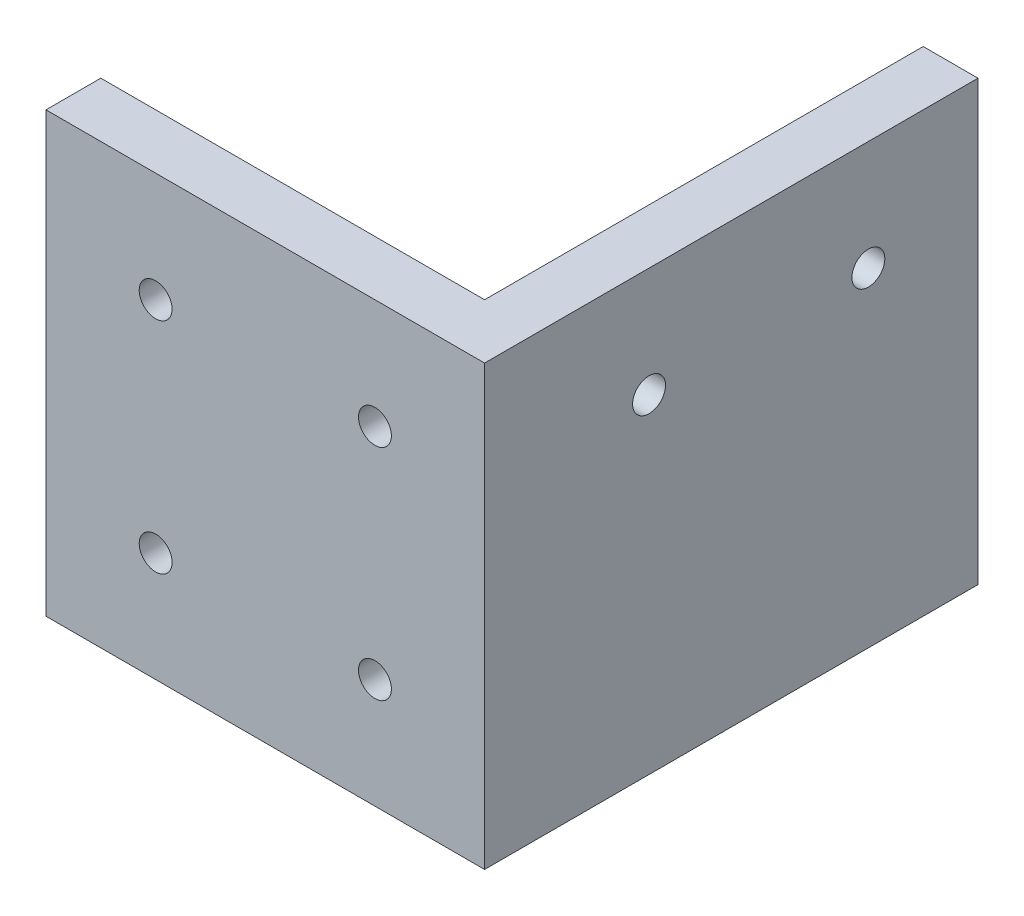
SolidWorks part; units mm, degrees
ref_plane "Front Plane" through (0, 0, 0) normal (0, 0, 1) x (1, 0, 0)
ref_plane "Top Plane" through (0, 0, 0) normal (0, 1, 0) x (1, 0, 0)
ref_plane "Right Plane" through (0, 0, 0) normal (1, 0, 0) x (0, 0, -1)
sketch "Sketch1" plane through (0, 0, 0) normal (0, 0, 1) x (1, 0, 0)
  line L0 (0, 0) -> (0, 95)
  line L1 (0, 95) -> (20, 95)
  line L2 (20, 95) -> (20, 75)
  line L3 (20, 75) -> (40, 75)
  line L4 (40, 75) -> (40, 80)
  line L5 (40, 80) -> (50, 80)
  line L6 (50, 80) -> (50, 75)
  line L7 (50, 75) -> (70, 75)
  line L8 (70, 75) -> (70, 80)
  line L9 (70, 80) -> (80, 80)
  line L10 (80, 80) -> (80, 15)
  line L11 (80, 15) -> (445, 15)
  line L23 (237.9167, 0) -> (0, 0)
  line L24 (262.5, 146.857) -> (262.5, -30.5268)
  line L25 (287.0833, 0) -> (525, 0)
  line L26 (445, 80) -> (445, 15)
  line L27 (455, 80) -> (445, 80)
  line L28 (455, 75) -> (455, 80)
  line L29 (475, 75) -> (455, 75)
  line L30 (485, 80) -> (475, 80)
  line L31 (485, 75) -> (485, 80)
  line L32 (505, 75) -> (485, 75)
  line L33 (505, 95) -> (505, 75)
  line L34 (525, 95) -> (505, 95)
  line L35 (525, 0) -> (525, 95)
  line L36 (475, 75) -> (475, 80)
  line L37 (237.9167, 0) -> (287.0833, 0)
  point P19 (262.5, 15)
  dimension "D1" = 10
  dimension "D2" = 10
  dimension "D3" = 182.5
  dimension "D4" = 20
  dimension "D5" = 20
  dimension "D6" = 20
  dimension "D7" = 20
  dimension "D8" = 5
  dimension "D9" = 5
  dimension "D10" = 65
  dimension "D11" = 80
  dimension "D12" = 95
extrude "Boss-Extrude1" add sketch "Sketch1" along normal blind 597.1 contours L23 L37 L24 L11 L10 L9 L8 L7 L6 L5 L4 L3 L2 L1 L0 | L24 L37 L25 L35 L34 L33 L32 L31 L30 L36 L29 L28 L27 L26 L11
sketch "Sketch2" plane through (0, 15, 0) normal (0, 1, 0) x (1, 0, 0)
  line L0 (80, 0) -> (445, 0) construction
  line L1 (187.3, 0) -> (252.5, 0)
  line L2 (187.3, 0) -> (187.3, -400)
  line L3 (187.3, -400) -> (252.5, -400)
  line L4 (252.5, 0) -> (252.5, -400)
  line L5 (80, -597.1) -> (445, -597.1) construction
  line L6 (272.5, -597.1) -> (337.7, -597.1)
  line L7 (272.5, -597.1) -> (272.5, -197.1)
  line L8 (272.5, -197.1) -> (337.7, -197.1)
  line L9 (337.7, -597.1) -> (337.7, -197.1)
  line L10 (445, -597.1) -> (445, 0) construction
  dimension "D1" = 400
  dimension "D2" = 400
  dimension "D3" = 65.2
  dimension "D4" = 65.2
  dimension "D5" = 20
  dimension "D6" = 107.3
extrude "Cut-Extrude1" cut sketch "Sketch2" against normal through all
sketch "Sketch3" plane through (0, 15, 0) normal (0, 1, 0) x (1, 0, 0)
  line L1 (80, 0) -> (445, 0)
  line L2 (80, 0) -> (80, -597.1)
  line L3 (80, -597.1) -> (445, -597.1)
  line L4 (445, 0) -> (445, -597.1)
  line L5 (187.3, 0) -> (252.5, 0)
  line L6 (187.3, 0) -> (187.3, -400)
  line L7 (187.3, -400) -> (252.5, -400)
  line L8 (252.5, 0) -> (252.5, -400)
  line L9 (272.5, -197.1) -> (337.7, -197.1)
  line L10 (272.5, -197.1) -> (272.5, -597.1)
  line L11 (272.5, -597.1) -> (337.7, -597.1)
  line L12 (337.7, -197.1) -> (337.7, -597.1)
  line M1 (187.3, -400) -> (187.3, 0)
  line M2 (187.3, 0) -> (80, 0)
  line M3 (80, 0) -> (80, -597.1)
  line M4 (80, -597.1) -> (272.5, -597.1)
  line M5 (272.5, -597.1) -> (272.5, -197.1)
  line M6 (272.5, -197.1) -> (337.7, -197.1)
  line M7 (337.7, -197.1) -> (337.7, -597.1)
  line M8 (337.7, -597.1) -> (445, -597.1)
  line M9 (445, -597.1) -> (445, 0)
  line M10 (445, 0) -> (252.5, 0)
  line M11 (252.5, 0) -> (252.5, -400)
  line M12 (252.5, -400) -> (187.3, -400)
extrude "Boss-Extrude2" add sketch "Sketch3" along normal blind 8 contours M12 M1 M2 M3 M4 M5 M6 M7 M8 M9 M10 M11
sketch "Sketch4" plane through (0, 0, 0) normal (0, -1, 0) x (1, 0, 0)
  line L1 (0, 597.1) -> (525, 597.1)
  line L2 (0, 597.1) -> (0, 0)
  line L3 (0, 0) -> (525, 0)
  line L4 (525, 597.1) -> (525, 0)
extrude "Boss-Extrude3" add sketch "Sketch4" along normal blind 7
sketch "Sketch5" plane through (0, 23, 0) normal (0, 1, 0) x (1, 0, 0)
  line L1 (80, 0) -> (445, 0)
  line L2 (80, 0) -> (80, -597.1)
  line L3 (80, -597.1) -> (445, -597.1)
  line L4 (445, 0) -> (445, -597.1)
extrude "Cut-Extrude2" cut sketch "Sketch5" against normal blind 10
sketch "Sketch6" plane through (525, 0, 0) normal (1, 0, 0) x (0, 0, -1)
  line L0 (-597.1, 95) -> (0, 95) construction
  line L1 (-324.55, 95) -> (-272.55, 95)
  line L2 (-324.55, 95) -> (-324.55, 55)
  line L3 (-324.55, 55) -> (-272.55, 55)
  line L4 (-272.55, 95) -> (-272.55, 55)
  line L6 (-597.1, -7) -> (-597.1, 95) construction
  circle A0 centre (-318.55, 79) radius 2.125
  circle A1 centre (-278.55, 79) radius 2.125
  circle A2 centre (-278.55, 63) radius 2.125
  circle A3 centre (-318.55, 63) radius 2.125
  circle A4 centre (-318.55, 79) radius 2.125
  circle A5 centre (-278.55, 79) radius 2.125
  circle A6 centre (-278.55, 63) radius 2.125
  circle A7 centre (-318.55, 63) radius 2.125
  dimension "D4" = 4.25
  dimension "D1" = 52
  dimension "D2" = 40
  dimension "D3" = 272.55
  dimension "D5" = 40
  dimension "D6" = 40
  dimension "D7" = 16
  dimension "D8" = 16
  dimension "D9" = 6
  dimension "D10" = 8
extrude "Cut-Extrude3" cut sketch "Sketch6" against normal up to next contours A0 | A3 | A2 | A1
cosmetic thread "Cosmetic Thread5" parameters "D2"=5.5
cosmetic thread "Cosmetic Thread6" parameters "D2"=5.5
cosmetic thread "Cosmetic Thread7" parameters "D2"=5.5
cosmetic thread "Cosmetic Thread8" parameters "D2"=5.5
sketch "Sketch7" plane through (0, 75, 0) normal (0, 1, 0) x (1, 0, 0)
  line L1 (485, 0) -> (505, 0)
  line L2 (485, 0) -> (485, -597.1)
  line L3 (485, -597.1) -> (505, -597.1)
  line L4 (505, 0) -> (505, -597.1)
extrude "Cut-Extrude4" cut sketch "Sketch7" against normal blind 5
sketch "Sketch8" plane through (445, 0, 0) normal (-1, 0, 0) x (0, 0, 1)
  line L0 (597.1, 80) -> (0, 80) construction
  line L1 (269.8676, 50) -> (324.923, 50)
  line L2 (269.8676, 50) -> (269.8676, 70)
  line L3 (269.8676, 70) -> (324.923, 70)
  line L4 (324.923, 50) -> (324.923, 70)
  dimension "D1" = 20
  dimension "D2" = 55.0555
  dimension "D3" = 10
extrude "Cut-Extrude6" cut sketch "Sketch8" against normal blind 60
sketch "Sketch13" plane through (0, 50, 0) normal (0, 1, 0) x (1, 0, 0)
  line L0 (445, -269.8676) -> (445, -324.923) construction
  line L1 (445, -290.3007) -> (485, -290.3007)
  line L2 (445, -290.3007) -> (445, -305.3007)
  line L3 (445, -305.3007) -> (485, -305.3007)
  line L4 (485, -290.3007) -> (485, -305.3007)
  dimension "D1" = 15
  dimension "D2" = 40
extrude "Boss-Extrude4" add sketch "Sketch13" along normal up to next
sketch "Sketch14" plane through (0, 75, 0) normal (0, 1, 0) x (1, 0, 0)
  line L1 (20, 0) -> (40, 0)
  line L2 (20, 0) -> (20, -597.1)
  line L3 (20, -597.1) -> (40, -597.1)
  line L4 (40, 0) -> (40, -597.1)
extrude "Cut-Extrude7" cut sketch "Sketch14" against normal blind 5
sketch "Sketch15" plane through (0, 0, 0) normal (-1, 0, 0) x (0, 0, 1)
  line L0 (597.1, 95) -> (0, 95) construction
  line L1 (10, 95) -> (37, 95)
  line L2 (10, 95) -> (10, 49.6)
  line L3 (10, 49.6) -> (37, 49.6)
  line L4 (37, 95) -> (37, 49.6)
  line L5 (0, -7) -> (0, 95) construction
  line L10 (298.55, -7) -> (298.55, 95)
  line L11 (597.1, -7) -> (0, -7) construction
  line L12 (587.1, 49.6) -> (560.1, 49.6)
  line L13 (587.1, 95) -> (560.1, 95)
  line L14 (587.1, 95) -> (587.1, 49.6)
  line L15 (560.1, 95) -> (560.1, 49.6)
  circle A0 centre (13.5, 82.3) radius 1.33
  circle A1 centre (33.5, 82.3) radius 1.33
  circle A2 centre (33.5, 62.3) radius 1.33
  circle A3 centre (13.5, 62.3) radius 1.33
  circle A4 centre (563.6, 62.3) radius 1.33
  circle A5 centre (563.6, 82.3) radius 1.33
  circle A6 centre (583.6, 82.3) radius 1.33
  circle A7 centre (583.6, 62.3) radius 1.33
  circle A8 centre (13.5, 82.3) radius 1.33
  circle A9 centre (33.5, 82.3) radius 1.33
  circle A10 centre (33.5, 62.3) radius 1.33
  circle A11 centre (13.5, 62.3) radius 1.33
  dimension "D2" = 2.66
  dimension "D1" = 10
  dimension "D3" = 45.4
  dimension "D4" = 27
  dimension "D5" = 20
  dimension "D6" = 20
  dimension "D7" = 20
  dimension "D8" = 20
  dimension "D9" = 3.5
  dimension "D10" = 12.7
extrude "Cut-Extrude8" cut sketch "Sketch15" against normal up to next contours A0 | A1 | A3 | A2 | A5 | A7 | A4 | A6
cosmetic thread "Cosmetic Thread9" parameters "D2"=3.2
cosmetic thread "Cosmetic Thread10" parameters "D2"=3.2
cosmetic thread "Cosmetic Thread11" parameters "D2"=3.2
cosmetic thread "Cosmetic Thread12" parameters "D2"=3.2
cosmetic thread "Cosmetic Thread13" parameters "D2"=3.2
cosmetic thread "Cosmetic Thread14" parameters "D2"=3.2
cosmetic thread "Cosmetic Thread15" parameters "D2"=3.2
cosmetic thread "Cosmetic Thread16" parameters "D2"=3.2
sketch "Sketch16" plane through (80, 0, 0) normal (1, 0, 0) x (0, 0, -1)
  line L0 (-597.1, 80) -> (-597.1, 13) construction
  line L1 (-592.1, 70) -> (-557.1, 70)
  line L2 (-592.1, 70) -> (-592.1, 55)
  line L3 (-592.1, 55) -> (-557.1, 55)
  line L4 (-557.1, 70) -> (-557.1, 55)
  line L5 (-597.1, 80) -> (0, 80) construction
  line L6 (0, 80) -> (0, 13) construction
  line L7 (-40, 55) -> (-5, 55)
  line L8 (-40, 55) -> (-40, 70)
  line L9 (-40, 70) -> (-5, 70)
  line L10 (-5, 55) -> (-5, 70)
  dimension "D1" = 5
  dimension "D2" = 15
  dimension "D3" = 10
  dimension "D4" = 35
  dimension "D5" = 10
  dimension "D6" = 5
  dimension "D7" = 35
  dimension "D8" = 15
extrude "Cut-Extrude9" cut sketch "Sketch16" against normal blind 60
sketch "Sketch17" plane through (0, -7, 0) normal (0, -1, 0) x (1, 0, 0)
  line L0 (525, 0) -> (525, 597.1) construction
  line L1 (465, 373.55) -> (525, 373.55)
  line L2 (465, 373.55) -> (465, 223.55)
  line L3 (465, 223.55) -> (525, 223.55)
  line L4 (525, 373.55) -> (525, 223.55)
  line L5 (525, 597.1) -> (0, 597.1) construction
  dimension "D1" = 150
  dimension "D2" = 223.55
  dimension "D3" = 60
extrude "Cut-Extrude10" cut sketch "Sketch17" against normal blind 40
sketch "Sketch18" plane through (0, 13, 0) normal (0, 1, 0) x (1, 0, 0)
  line L1 (427, -286.05) -> (415, -286.05)
  line L2 (427, -286.05) -> (427, -302.05)
  line L3 (427, -302.05) -> (415, -302.05)
  line L4 (415, -286.05) -> (415, -302.05)
  line L5 (417, -286.05) -> (425, -286.05)
  line L6 (445, 0) -> (252.5, 0) construction
  line L7 (417, -286.05) -> (417, -279.05)
  line L8 (445, -597.1) -> (445, 0) construction
  line L9 (417, -279.05) -> (425, -279.05)
  line L10 (425, -286.05) -> (425, -279.05)
  line L11 (417, -302.05) -> (425, -302.05)
  line L12 (417, -302.05) -> (417, -309.05)
  line L13 (417, -309.05) -> (425, -309.05)
  line L14 (425, -302.05) -> (425, -309.05)
  dimension "D1" = 12
  dimension "D2" = 16
  dimension "D3" = 286.05
  dimension "D4" = 30
  dimension "D5" = 8
  dimension "D6" = 7
  dimension "D7" = 2
  dimension "D8" = 8
  dimension "D9" = 7
  dimension "D10" = 2
extrude "Cut-Extrude11" cut sketch "Sketch18" against normal through all contours L1 L4 L3 L2
sketch "Sketch19" plane through (0, 13, 0) normal (0, 1, 0) x (1, 0, 0)
  line L0 (427, -286.05) -> (415, -286.05) construction
  line L1 (417, -286.05) -> (425, -286.05)
  line L2 (417, -286.05) -> (417, -279.05)
  line L3 (417, -279.05) -> (425, -279.05)
  line L4 (425, -286.05) -> (425, -279.05)
  line L5 (427, -302.05) -> (415, -302.05) construction
  line L6 (417, -302.05) -> (425, -302.05)
  line L7 (417, -302.05) -> (417, -309.05)
  line L8 (417, -309.05) -> (425, -309.05)
  line L9 (425, -302.05) -> (425, -309.05)
  line L10 (415, -286.05) -> (415, -302.05) construction
  dimension "D1" = 8
  dimension "D2" = 8
  dimension "D3" = 7
  dimension "D4" = 7
  dimension "D5" = 2
  dimension "D6" = 2
extrude "Cut-Extrude12" cut sketch "Sketch19" against normal blind 10
sketch "Sketch20" plane through (525, 0, 0) normal (1, 0, 0) x (0, 0, -1)
  circle A0 centre (-318.55, 79) radius 2.7599
  circle A1 centre (-318.55, 63) radius 2.758
  circle A2 centre (-278.55, 63) radius 2.7761
  circle A3 centre (-278.55, 79) radius 2.7514
extrude "Cut-Extrude13" cut sketch "Sketch20" against normal up to next
sketch "Sketch21" plane through (0, 0, 0) normal (-1, 0, 0) x (0, 0, 1)
  circle A0 centre (13.5, 82.3) radius 1.6434
  circle A1 centre (13.5, 62.3) radius 1.6389
  circle A2 centre (33.5, 62.3) radius 1.6445
  circle A3 centre (33.5, 82.3) radius 1.706
  circle A4 centre (563.6, 62.3) radius 1.6454
  circle A5 centre (583.6, 62.3) radius 1.6466
  circle A6 centre (583.6, 82.3) radius 1.6613
  circle A7 centre (563.6, 82.3) radius 1.7012
extrude "Cut-Extrude14" cut sketch "Sketch21" against normal up to next
sketch "Sketch22" plane through (445, 0, 0) normal (-1, 0, 0) x (0, 0, 1)
  line L1 (290.3007, 70) -> (305.3007, 70)
  line L2 (290.3007, 70) -> (290.3007, 50)
  line L3 (290.3007, 50) -> (305.3007, 50)
  line L4 (305.3007, 70) -> (305.3007, 50)
extrude "Cut-Extrude15" cut sketch "Sketch22" against normal up to next
sketch "Sketch24" plane through (525, 0, 0) normal (1, 0, 0) x (0, 0, -1)
  line L0 (-597.1, -7) -> (-597.1, 95) construction
  line L1 (-597.1, 95) -> (0, 95) construction
  line L4 (0, -7) -> (0, 95) construction
  circle A0 centre (-583.6, 82.3) radius 1.5
  circle A1 centre (-563.6, 82.3) radius 1.5
  circle A2 centre (-583.6, 62.3) radius 1.5
  circle A3 centre (-563.6, 62.3) radius 1.5
  circle A4 centre (-33.5, 82.3) radius 1.5
  circle A5 centre (-13.5, 82.3) radius 1.5
  circle A6 centre (-13.5, 62.3) radius 1.5
  circle A7 centre (-33.5, 62.3) radius 1.5
  dimension "D1" = 3
  dimension "D2" = 13.5
  dimension "D3" = 12.7
  dimension "D4" = 20
  dimension "D5" = 13.5
  dimension "D6" = 12.7
  dimension "D7" = 20
  dimension "D8" = 20
  dimension "D9" = 20
  dimension "D10" = 13.5
  dimension "D11" = 20
  dimension "D12" = 20
  dimension "D13" = 20
  dimension "D14" = 20
  dimension "D15" = 12.7
  dimension "D16" = 13.5
  dimension "D17" = 12.7
extrude "Cut-Extrude16" cut sketch "Sketch24" against normal up to next
sketch "Sketch27" plane through (445, 0, 0) normal (-1, 0, 0) x (0, 0, 1)
  line L0 (597.1, 80) -> (0, 80) construction
  line L1 (592.1, 70) -> (557.1, 70)
  line L2 (592.1, 70) -> (592.1, 55)
  line L3 (592.1, 55) -> (557.1, 55)
  line L4 (557.1, 70) -> (557.1, 55)
  line L5 (597.1, 80) -> (597.1, 13) construction
  dimension "D1" = 10
  dimension "D2" = 5
  dimension "D3" = 35
  dimension "D4" = 15
extrude "Cut-Extrude17" cut sketch "Sketch27" against normal blind 60
sketch "Sketch28" plane through (445, 0, 0) normal (-1, 0, 0) x (0, 0, 1)
  line L1 (0, 80) -> (40, 80)
  line L2 (0, 80) -> (0, 55)
  line L3 (0, 55) -> (40, 55)
  line L4 (40, 80) -> (40, 55)
  line L5 (40, 55) -> (5, 55)
  line L6 (40, 55) -> (40, 70)
  line L7 (40, 70) -> (5, 70)
  line L8 (5, 55) -> (5, 70)
  circle M9 centre (13.5, 62.3) radius 1.5
  circle M10 centre (33.5, 62.3) radius 1.5
  dimension "D1" = 40
  dimension "D2" = 25
  dimension "D3" = 15
  dimension "D4" = 35
extrude "Cut-Extrude18" cut sketch "Sketch28" against normal blind 60 contours L8 L3 L4 L7 M10 M9
sketch "Sketch29" plane through (0, -7, 0) normal (0, -1, 0) x (1, 0, 0)
  line L0 (0, 597.1) -> (0, 0) construction
  line L1 (0, 373.55) -> (60, 373.55)
  line L2 (0, 373.55) -> (0, 223.55)
  line L3 (0, 223.55) -> (60, 223.55)
  line L4 (60, 373.55) -> (60, 223.55)
  dimension "D1" = 60
  dimension "D2" = 150
extrude "Cut-Extrude19" cut sketch "Sketch29" against normal blind 40
sketch "Sketch33" plane through (0, 0, 0) normal (-1, 0, 0) x (0, 0, 1)
  line L0 (597.1, 95) -> (0, 95) construction
  line L1 (597.1, -7) -> (597.1, 95) construction
  circle A0 centre (318.55, 79) radius 2.5
  circle A1 centre (319.3565, 63) radius 2.5
  circle A2 centre (278.55, 79) radius 2.5
  circle A3 centre (279.3565, 63) radius 2.5
  dimension "D1" = 5
  dimension "D2" = 40
  dimension "D3" = 16
  dimension "D4" = 40
  dimension "D5" = 16
  dimension "D6" = 16
  dimension "D7" = 278.55
extrude "Cut-Extrude20" cut sketch "Sketch33" against normal up to next
sketch "Sketch37" plane through (80, 0, 0) normal (1, 0, 0) x (0, 0, -1)
  line L0 (-597.1, 80) -> (0, 80) construction
  line L1 (-327.18, 50) -> (-272.18, 50)
  line L2 (-327.18, 50) -> (-327.18, 70)
  line L3 (-327.18, 70) -> (-272.18, 70)
  line L4 (-272.18, 50) -> (-272.18, 70)
  line L5 (0, 80) -> (0, 13) construction
  dimension "D1" = 20
  dimension "D2" = 55
  dimension "D3" = 10
  dimension "D4" = 272.18
extrude "Cut-Extrude21" cut sketch "Sketch37" against normal blind 60
sketch "Sketch39" plane through (0, 0, 0) normal (-1, 0, 0) x (0, 0, 1)
  line L0 (597.1, 95) -> (0, 95) construction
  line L1 (3, 95) -> (8, 95)
  line L2 (3, 95) -> (3, 55)
  line L3 (3, 55) -> (8, 55)
  line L4 (8, 95) -> (8, 55)
  line L5 (0, -7) -> (0, 95) construction
  line L6 (597.1, -7) -> (597.1, 95) construction
  line L7 (589.1, 95) -> (594.1, 95)
  line L8 (589.1, 95) -> (589.1, 55)
  line L9 (589.1, 55) -> (594.1, 55)
  line L10 (594.1, 95) -> (594.1, 55)
  dimension "D1" = 3
  dimension "D2" = 5
  dimension "D3" = 40
  dimension "D4" = 3
  dimension "D5" = 5
  dimension "D6" = 40
extrude "Boss-Extrude6" add sketch "Sketch39" along normal blind 40
sketch "Sketch41" plane through (0, 0, 3) normal (0, 0, -1) x (-1, 0, 0)
  line L0 (40, 95) -> (0, 95) construction
  line L1 (40, 95) -> (40, 55) construction
  circle A0 centre (10, 85) radius 1.5
  circle A1 centre (30, 85) radius 1.5
  circle A2 centre (30, 65) radius 1.5
  circle A3 centre (10, 65) radius 1.5
  dimension "D1" = 3
  dimension "D2" = 20
  dimension "D3" = 20
  dimension "D4" = 20
  dimension "D5" = 20
  dimension "D6" = 10
  dimension "D7" = 10
  dimension "D8" = 10
extrude "Cut-Extrude22" cut sketch "Sketch41" against normal through all
sketch "Sketch42" plane through (80, 0, 0) normal (1, 0, 0) x (0, 0, -1)
  line L1 (-592.1, 70) -> (-557.1, 70)
  line L2 (-592.1, 70) -> (-592.1, 55)
  line L3 (-592.1, 55) -> (-557.1, 55)
  line L4 (-557.1, 70) -> (-557.1, 55)
  line L5 (-40, 70) -> (-5, 70)
  line L6 (-40, 70) -> (-40, 55)
  line L7 (-40, 55) -> (-5, 55)
  line L8 (-5, 70) -> (-5, 55)
extrude "Boss-Extrude7" add sketch "Sketch42" against normal blind 60
sketch "Sketch43" plane through (0, 0, 0) normal (-1, 0, 0) x (0, 0, 1)
  line L0 (589.1, 95) -> (8, 95) construction
  line L1 (8, 95) -> (49.1479, 95)
  line L2 (8, 95) -> (8, 53.381)
  line L3 (8, 53.381) -> (49.1479, 53.381)
  line L4 (49.1479, 95) -> (49.1479, 53.381)
  line L5 (546.6637, 95) -> (589.1, 95)
  line L6 (546.6637, 95) -> (546.6637, 55)
  line L7 (546.6637, 55) -> (589.1, 55)
  line L8 (589.1, 95) -> (589.1, 55)
extrude "Boss-Extrude8" add sketch "Sketch43" against normal blind 20
sketch "Sketch44" plane through (525, 0, 0) normal (1, 0, 0) x (0, 0, -1)
  line L0 (-597.1, 95) -> (0, 95) construction
  line L1 (-597.1, 95) -> (-547.4631, 95)
  line L2 (-597.1, 95) -> (-597.1, 48.775)
  line L3 (-597.1, 48.775) -> (-547.4631, 48.775)
  line L4 (-547.4631, 95) -> (-547.4631, 48.775)
  line L5 (-1.3119, 95) -> (-48.1855, 95)
  line L6 (-1.3119, 95) -> (-1.3119, 48.775)
  line L7 (-1.3119, 48.775) -> (-48.1855, 48.775)
  line L8 (-48.1855, 95) -> (-48.1855, 48.775)
extrude "Boss-Extrude9" add sketch "Sketch44" against normal blind 20
sketch "Sketch45" plane through (445, 0, 0) normal (-1, 0, 0) x (0, 0, 1)
  line L1 (5, 70) -> (40, 70)
  line L2 (5, 70) -> (5, 55)
  line L3 (5, 55) -> (40, 55)
  line L4 (40, 70) -> (40, 55)
  line L5 (557.1, 70) -> (592.1, 70)
  line L6 (557.1, 70) -> (557.1, 55)
  line L7 (557.1, 55) -> (592.1, 55)
  line L8 (592.1, 70) -> (592.1, 55)
extrude "Boss-Extrude10" add sketch "Sketch45" against normal blind 60
sketch "Sketch46" plane through (525, 0, 0) normal (1, 0, 0) x (0, 0, -1)
  line L0 (-597.1, 95) -> (0, 95) construction
  line L1 (-594.1, 95) -> (-589.1, 95)
  line L2 (-594.1, 95) -> (-594.1, 55)
  line L3 (-594.1, 55) -> (-589.1, 55)
  line L4 (-589.1, 95) -> (-589.1, 55)
  line L5 (-597.1, -7) -> (-597.1, 95) construction
  line L6 (0, -7) -> (0, 95) construction
  line L7 (-8, 95) -> (-3, 95)
  line L8 (-8, 95) -> (-8, 55)
  line L9 (-8, 55) -> (-3, 55)
  line L10 (-3, 95) -> (-3, 55)
  dimension "D1" = 5
  dimension "D2" = 40
  dimension "D3" = 3
  dimension "D4" = 5
  dimension "D5" = 3
  dimension "D6" = 40
extrude "Boss-Extrude11" add sketch "Sketch46" along normal blind 40
sketch "Sketch47" plane through (0, 0, 3) normal (0, 0, -1) x (-1, 0, 0)
  line L0 (-565, 95) -> (-525, 95) construction
  line L1 (-565, 55) -> (-565, 95) construction
  circle A0 centre (-555, 85) radius 1.5
  circle A1 centre (-535, 84.6583) radius 1.5
  circle A2 centre (-535, 64.6583) radius 1.5
  circle A3 centre (-555, 65) radius 1.5
  dimension "D7" = 3
  dimension "D1" = 10
  dimension "D2" = 10
  dimension "D3" = 20
  dimension "D4" = 20
  dimension "D5" = 20
  dimension "D6" = 20
  dimension "D8" = 10
extrude "Cut-Extrude23" cut sketch "Sketch47" against normal through all
fillet "Fillet1" radius 5 1 edges at (0, 75, 8)
fillet "Fillet2" radius 5 3 edges at (525, 75, 8) (525, 75, 589.1) (0, 75, 589.1)
sketch "Sketch51" plane through (0, 0, 0) normal (-1, 0, 0) x (0, 0, 1)
  line L0 (584.1, 95) -> (13, 95) construction
  line L1 (48, 95) -> (8, 95)
  line L2 (48, 95) -> (48, 55)
  line L3 (48, 55) -> (8, 55)
  line L4 (8, 95) -> (8, 55)
  line L5 (8, 55) -> (8, 95) construction
  line L6 (8, 55) -> (8, 95) construction
  dimension "D1" = 40
extrude "Boss-Extrude12" add sketch "Sketch51" along normal blind 5
sketch "Sketch52" plane through (-5, 0, 0) normal (-1, 0, 0) x (0, 0, 1)
  line L0 (8, 55) -> (8, 95) construction
  line L1 (48, 95) -> (8, 95) construction
  circle A0 centre (18, 85) radius 3
  circle A1 centre (28, 85) radius 3
  circle A2 centre (38, 85) radius 3
  dimension "D1" = 6
  dimension "D2" = 10
  dimension "D3" = 10
  dimension "D4" = 10
  dimension "D5" = 10
extrude "Cut-Extrude26" cut sketch "Sketch52" against normal through all
sketch "Sketch53" plane through (-5, 0, 0) normal (-1, 0, 0) x (0, 0, 1)
  circle A0 centre (28, 85) radius 3.2804
extrude "Boss-Extrude13" add sketch "Sketch53" against normal through all
sketch "Sketch54" plane through (565, 0, 0) normal (1, 0, 0) x (0, 0, -1)
  circle A0 centre (-28, 85) radius 3.2804
extrude "Cut-Extrude27" cut sketch "Sketch54" against normal blind 40
sketch "Sketch55" plane through (0, 0, 0) normal (0, 0, -1) x (-1, 0, 0)
  line L0 (-20, 95) -> (-20, 70) construction
  line L1 (-505, 95) -> (-20, 95)
  line L2 (-505, 95) -> (-505, 80.5212)
  line L3 (-505, 80.5212) -> (-20, 80.5212)
  line L4 (-20, 95) -> (-20, 80.5212)
extrude "Cut-Extrude28" cut sketch "Sketch55" against normal blind 40
sketch "Sketch57" plane through (0, 0, 0) normal (0, 0, -1) x (-1, 0, 0)
  line L1 (0, 95) -> (-723.1869, 95)
  line L2 (0, 95) -> (0, -65.7079)
  line L3 (0, -65.7079) -> (-723.1869, -65.7079)
  line L4 (-723.1869, 95) -> (-723.1869, -65.7079)
extrude "Cut-Extrude30" cut sketch "Sketch57" against normal through all
sketch "Sketch60" plane through (0, 0, 0) normal (1, 0, 0) x (0, 0, -1)
  line L1 (-3, 95) -> (37, 95)
  line L2 (-3, 95) -> (-3, 55)
  line L3 (-3, 55) -> (37, 55)
  line L4 (37, 95) -> (37, 55)
  dimension "D1" = 40
  dimension "D2" = 40
extrude "Boss-Extrude15" add sketch "Sketch60" against normal blind 5
sketch "Sketch61" plane through (0, 0, 0) normal (1, 0, 0) x (0, 0, -1)
  line L0 (-48, 95) -> (37, 95) construction
  line L1 (37, 55) -> (37, 95) construction
  circle A0 centre (7, 85) radius 3
  circle A1 centre (27, 85) radius 3
  dimension "D1" = 6
  dimension "D2" = 10
  dimension "D3" = 10
  dimension "D4" = 20
  dimension "D5" = 10
extrude "Cut-Extrude31" cut sketch "Sketch61" against normal blind 5
sketch "Sketch62" plane through (-5, 0, 0) normal (-1, 0, 0) x (0, 0, 1)
  line L1 (8, 95) -> (48, 95)
  line L2 (8, 95) -> (8, 55)
  line L3 (8, 55) -> (48, 55)
  line L4 (48, 95) -> (48, 55)
extrude "Cut-Extrude32" cut sketch "Sketch62" against normal blind 5
sketch "Sketch63" plane through (-5, 0, 0) normal (-1, 0, 0) x (0, 0, 1)
  circle A0 centre (-27, 85) radius 1.5
  circle A1 centre (-7, 85) radius 1.5
  circle A2 centre (-7, 85) radius 4.7009
  circle A3 centre (-27, 85) radius 5.7399
  dimension "D1" = 3
  dimension "D2" = 3
extrude "Boss-Extrude16" add sketch "Sketch63" against normal blind 5
sketch "Sketch64" plane through (-5, 0, 0) normal (-1, 0, 0) x (0, 0, 1)
  circle A0 centre (-27, 85) radius 3.5
  circle A1 centre (-7, 85) radius 3.5
  dimension "D1" = 7
  dimension "D2" = 7
extrude "Cut-Extrude33" cut sketch "Sketch64" against normal blind 1.5
